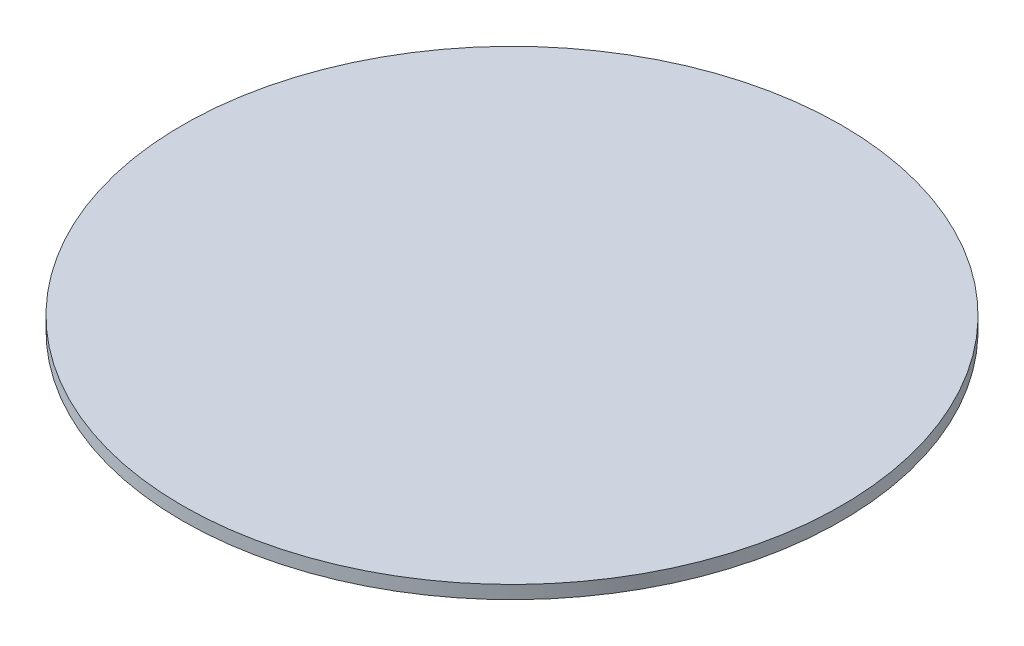
SolidWorks part; units mm, degrees
ref_plane "前视基准面" through (0, 0, 0) normal (0, 0, 1) x (1, 0, 0)
ref_plane "上视基准面" through (0, 0, 0) normal (0, 1, 0) x (1, 0, 0)
ref_plane "右视基准面" through (0, 0, 0) normal (1, 0, 0) x (0, 0, -1)
sketch "草图1" plane through (0, 0, 0) normal (0, 1, 0) x (1, 0, 0)
  circle A0 centre (0, 0) radius 150
  dimension "D1" = 300
extrude "凸台-拉伸1" add sketch "草图1" along normal blind 6
sketch "草图2" plane through (0, 6, 0) normal (0, 1, 0) x (1, 0, 0)
  circle A0 centre (0, 0) radius 100 construction
  dimension "D1" = 200
